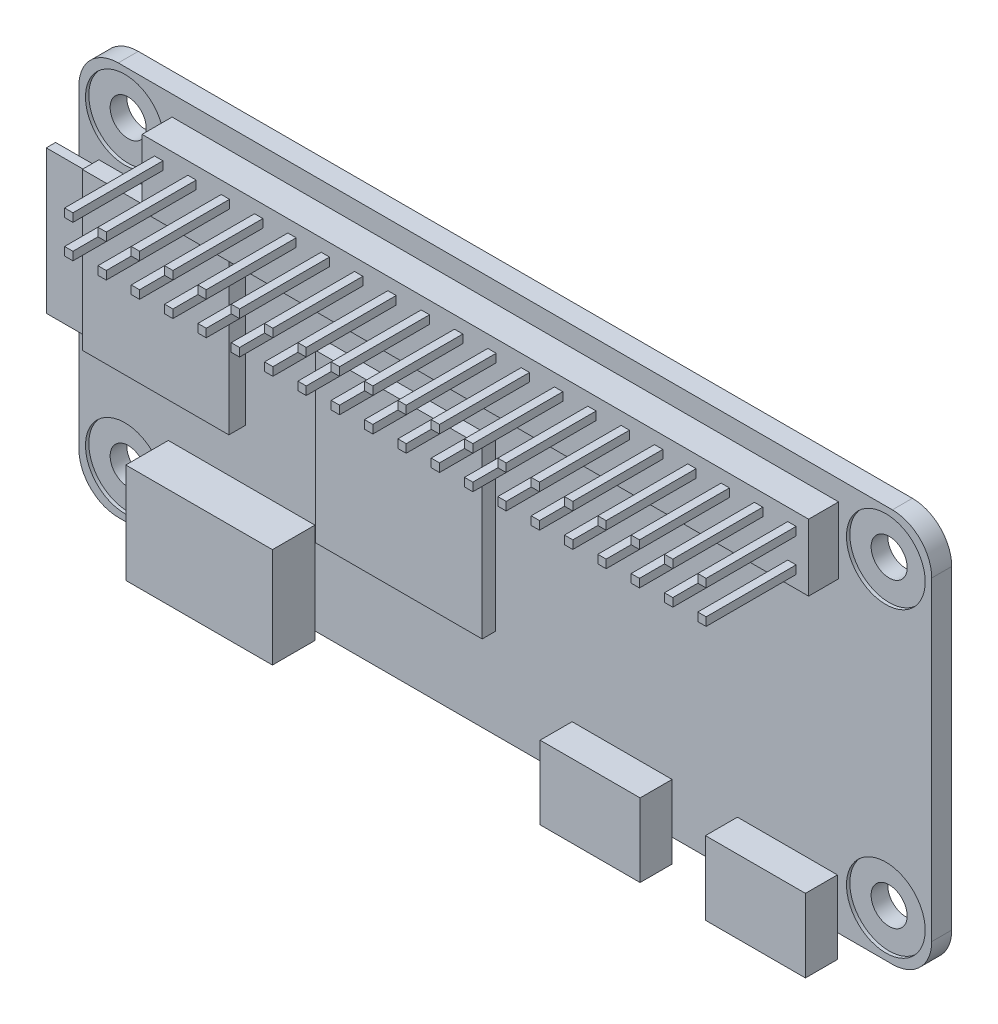
SolidWorks part; units mm, degrees
ref_plane "Front Plane" through (0, 0, 0) normal (0, 0, 1) x (1, 0, 0)
ref_plane "Top Plane" through (0, 0, 0) normal (0, 1, 0) x (1, 0, 0)
ref_plane "Right Plane" through (0, 0, 0) normal (1, 0, 0) x (0, 0, -1)
sketch "Sketch1" plane through (0, 0, 0) normal (0, 0, 1) x (1, 0, 0)
  line L1 (0, 0) -> (65, 0)
  line L2 (0, 0) -> (0, 30)
  line L3 (0, 30) -> (65, 30)
  line L4 (65, 0) -> (65, 30)
  dimension "D1" = 65
  dimension "D2" = 30
extrude "Boss-Extrude1" add sketch "Sketch1" along normal blind 1.524
fillet "Fillet1" radius 3 4 edges at (65, 30, 0.762) (65, 0, 0.762) (0, 0, 0.762) (0, 30, 0.762)
sketch "Sketch2" plane through (0, 0, 1.524) normal (0, 0, 1) x (1, 0, 0)
  line L0 (3.5, 3.5) -> (61.5, 3.5) construction
  line L1 (61.5, 3.5) -> (61.5, 26.5) construction
  line L2 (61.5, 26.5) -> (3.5, 26.5) construction
  line L3 (3.5, 26.5) -> (3.5, 3.5) construction
  line L4 (32.5, 26.5) -> (32.5, 30) construction
  line L5 (62, 30) -> (3, 30) construction
  line L6 (0, 15) -> (3.5, 15) construction
  line L7 (0, 27) -> (0, 3) construction
  circle A0 centre (3.5, 26.5) radius 1.375
  circle A1 centre (61.5, 26.5) radius 1.375
  circle A2 centre (61.5, 3.5) radius 1.375
  circle A3 centre (3.5, 3.5) radius 1.375
  dimension "D1" = 2.75
  dimension "D2" = 23
  dimension "D3" = 58
extrude "Cut-Extrude1" cut sketch "Sketch2" against normal through all
sketch "Sketch3" plane through (0, 0, 1.524) normal (0, 0, 1) x (1, 0, 0)
  circle A0 centre (3.5, 26.5) radius 3
  circle A1 centre (61.5, 26.5) radius 3
  circle A2 centre (61.5, 3.5) radius 3
  circle A3 centre (3.5, 3.5) radius 3
  dimension "D1" = 6
extrude "Cut-Extrude2" cut sketch "Sketch3" against normal blind 0.254
sketch "Sketch4" plane through (0, 0, 1.524) normal (0, 0, 1) x (1, 0, 0)
  line L0 (41.4, 3.81) -> (41.4, -1.778) construction
  line L1 (37.59, 3.81) -> (45.21, 3.81)
  line L2 (37.59, 3.81) -> (37.59, -1.778)
  line L3 (37.59, -1.778) -> (45.21, -1.778)
  line L4 (45.21, 3.81) -> (45.21, -1.778)
  line L5 (50.19, 3.81) -> (57.81, 3.81)
  line L6 (50.19, 3.81) -> (50.19, -1.778)
  line L7 (50.19, -1.778) -> (57.81, -1.778)
  line L8 (57.81, 3.81) -> (57.81, -1.778)
  line L9 (54, 3.81) -> (54, -1.778) construction
  line L10 (3, 0) -> (62, 0) construction
  line L11 (0, 27) -> (0, 3) construction
  dimension "D1" = 5.588
  dimension "D2" = 5.588
  dimension "D3" = 7.62
  dimension "D4" = 7.62
  dimension "D5" = 1.778
  dimension "D6" = 1.778
  dimension "D7" = 41.4
  dimension "D8" = 54
extrude "Boss-Extrude2" add sketch "Sketch4" along normal offset from surface (2.4384 mm away) 3.9624 up to face at (4.875, 3.5, 0)
sketch "Sketch5" plane through (0, 0, 1.524) normal (0, 0, 1) x (1, 0, 0)
  line L0 (12.4, 6.985) -> (12.4, -0.635) construction
  line L1 (6.812, 6.985) -> (17.988, 6.985)
  line L2 (6.812, 6.985) -> (6.812, -0.635)
  line L3 (6.812, -0.635) -> (17.988, -0.635)
  line L4 (17.988, 6.985) -> (17.988, -0.635)
  line L5 (3, 0) -> (37.59, 0) construction
  line L6 (0, 27) -> (0, 3) construction
  point P6 (17.5272, -3.62)
  dimension "D1" = 7.62
  dimension "D2" = 11.176
  dimension "D3" = 0.635
  dimension "D4" = 12.4
extrude "Boss-Extrude3" add sketch "Sketch5" along normal offset from surface (3.2385 mm away) 4.7625 up to face at (4.875, 3.5, 0)
sketch "Sketch6" plane through (0, 0, 1.524) normal (0, 0, 1) x (1, 0, 0)
  line L0 (0, 27) -> (0, 3) construction
  line L1 (1.524, 22.869) -> (12.7, 22.869)
  line L2 (1.524, 22.869) -> (1.524, 10.931)
  line L3 (1.524, 10.931) -> (12.7, 10.931)
  line L4 (12.7, 22.869) -> (12.7, 10.931)
  line L5 (1.524, 16.9) -> (12.7, 16.9) construction
  line L6 (3, 0) -> (6.812, 0) construction
  dimension "D1" = 11.938
  dimension "D2" = 11.176
  dimension "D3" = 1.524
  dimension "D4" = 16.9
extrude "Boss-Extrude4" add sketch "Sketch6" along normal offset from surface (1.27 mm away) 2.794 up to face at (4.875, 3.5, 0)
sketch "Sketch7" plane through (1.524, 0, 0) normal (-1, 0, 0) x (0, 0, 1)
  line L0 (1.524, 22.869) -> (1.524, 10.931) construction
  line L1 (1.524, 22.361) -> (2.2352, 22.361)
  line L2 (1.524, 22.361) -> (1.524, 11.439)
  line L3 (1.524, 11.439) -> (2.2352, 11.439)
  line L4 (2.2352, 22.361) -> (2.2352, 11.439)
  line L5 (2.2352, 16.9) -> (2.794, 16.9) construction
  line L6 (2.794, 10.931) -> (2.794, 22.869) construction
  dimension "D1" = 10.922
  dimension "D2" = 0.7112
extrude "Boss-Extrude7" add sketch "Sketch7" along normal blind 3.302
sketch "Sketch8" plane through (0, 0, 1.524) normal (0, 0, 1) x (1, 0, 0)
  line L0 (32.5, 23.396) -> (32.5, 28.476) construction
  line L1 (7.1, 28.476) -> (57.9, 28.476)
  line L2 (7.1, 28.476) -> (7.1, 23.396)
  line L3 (7.1, 23.396) -> (57.9, 23.396)
  line L4 (57.9, 28.476) -> (57.9, 23.396)
  line L5 (62, 30) -> (3, 30) construction
  circle A0 centre (3.5, 26.5) radius 1.375 construction
  dimension "D1" = 5.08
  dimension "D2" = 50.8
  dimension "D3" = 29
  dimension "D4" = 1.524
extrude "Boss-Extrude8" add sketch "Sketch8" along normal blind 2.286
sketch "Sketch9" plane through (0, 0, 3.81) normal (0, 0, 1) x (1, 0, 0)
  line L0 (7.1, 25.936) -> (57.9, 25.936) construction
  line L1 (8.0525, 27.5235) -> (8.6875, 27.5235)
  line L2 (8.0525, 27.5235) -> (8.0525, 26.8885)
  line L3 (8.0525, 26.8885) -> (8.6875, 26.8885)
  line L4 (8.6875, 27.5235) -> (8.6875, 26.8885)
  line L5 (8.0525, 24.9835) -> (8.6875, 24.9835)
  line L6 (8.0525, 24.9835) -> (8.0525, 24.3485)
  line L7 (8.0525, 24.3485) -> (8.6875, 24.3485)
  line L8 (8.6875, 24.9835) -> (8.6875, 24.3485)
  line L9 (7.1, 28.476) -> (7.1, 23.396) construction
  line L10 (57.9, 23.396) -> (57.9, 28.476) construction
  line L11 (8.37, 24.9835) -> (8.37, 25.936) construction
  line L12 (8.37, 25.936) -> (8.37, 26.8885) construction
  line L13 (8.0525, 27.206) -> (7.1, 27.206) construction
  line L14 (7.1, 28.476) -> (7.1, 23.396) construction
  line L15 (8.0525, 24.666) -> (7.1, 24.666) construction
  dimension "D1" = 0.635
  dimension "D2" = 0.635
  dimension "D3" = 2.54
  dimension "D4" = 1.27
extrude "Boss-Extrude9" add sketch "Sketch9" along normal blind 6.858
pattern_linear "LPattern1" count 20 spacing 2.54 along (1, 0, 0) of "Boss-Extrude9"
sketch "Sketch10" plane through (0, 0, 1.524) normal (0, 0, 1) x (1, 0, 0)
  line L0 (17.988, 0) -> (37.59, 0) construction
  line L1 (19.05, 19.558) -> (31.75, 19.558)
  line L2 (19.05, 19.558) -> (19.05, 6.858)
  line L3 (19.05, 6.858) -> (31.75, 6.858)
  line L4 (31.75, 19.558) -> (31.75, 6.858)
  line L5 (19.05, 19.558) -> (31.75, 6.858) construction
  line L6 (19.05, 6.858) -> (31.75, 19.558) construction
  line L7 (0, 11.439) -> (0, 3) construction
  point P0 (25.4, 13.208)
  point P5 (28.0571, 14.6328)
  dimension "D1" = 12.7
  dimension "D2" = 12.7
  dimension "D3" = 13.208
  dimension "D4" = 25.4
extrude "Boss-Extrude10" add sketch "Sketch10" along normal blind 1.016
